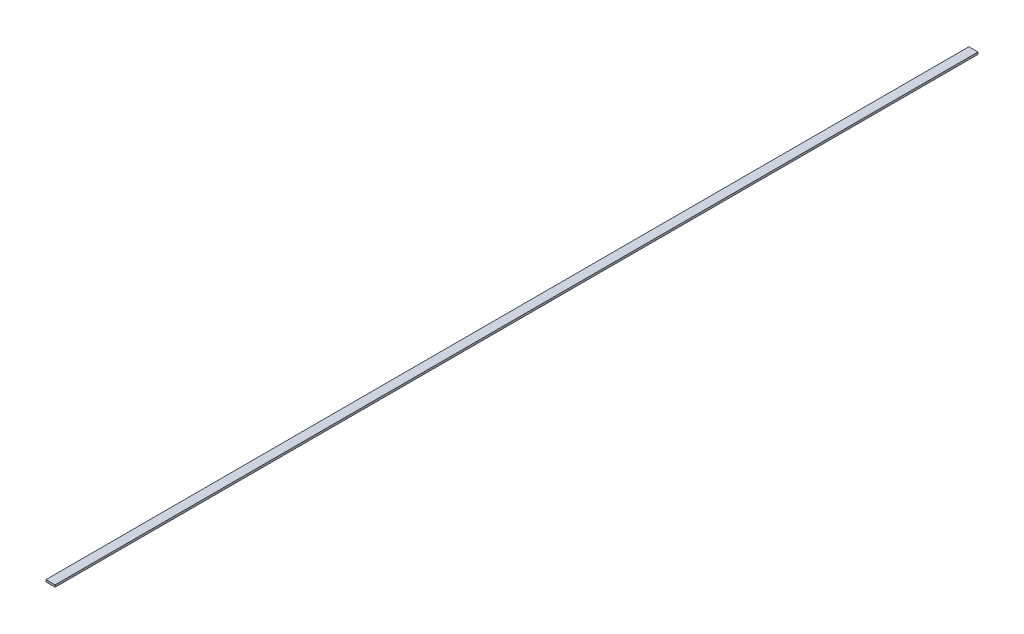
SolidWorks part; units mm, degrees
ref_plane "Front Plane" through (0, 0, 0) normal (0, 0, 1) x (1, 0, 0)
ref_plane "Top Plane" through (0, 0, 0) normal (0, 1, 0) x (1, 0, 0)
ref_plane "Right Plane" through (0, 0, 0) normal (1, 0, 0) x (0, 0, -1)
sketch "Sketch1" plane through (0, 0, 0) normal (0, 0, 1) x (1, 0, 0)
  line L0 (-1.5, 0.35) -> (1.5, 0.35)
  line L1 (1.5, 0.35) -> (1.5, -0.35)
  line L2 (-1.5, 0.35) -> (-1.5, -0.35)
  line L3 (-1.5, -0.35) -> (1.5, -0.35)
  point P2 (0, 0.35)
  point P4 (1.5, 0)
  dimension "D1" = 3
  dimension "D2" = 0.7
extrude "Boss-Extrude1" add sketch "Sketch1" along normal blind 304.8
